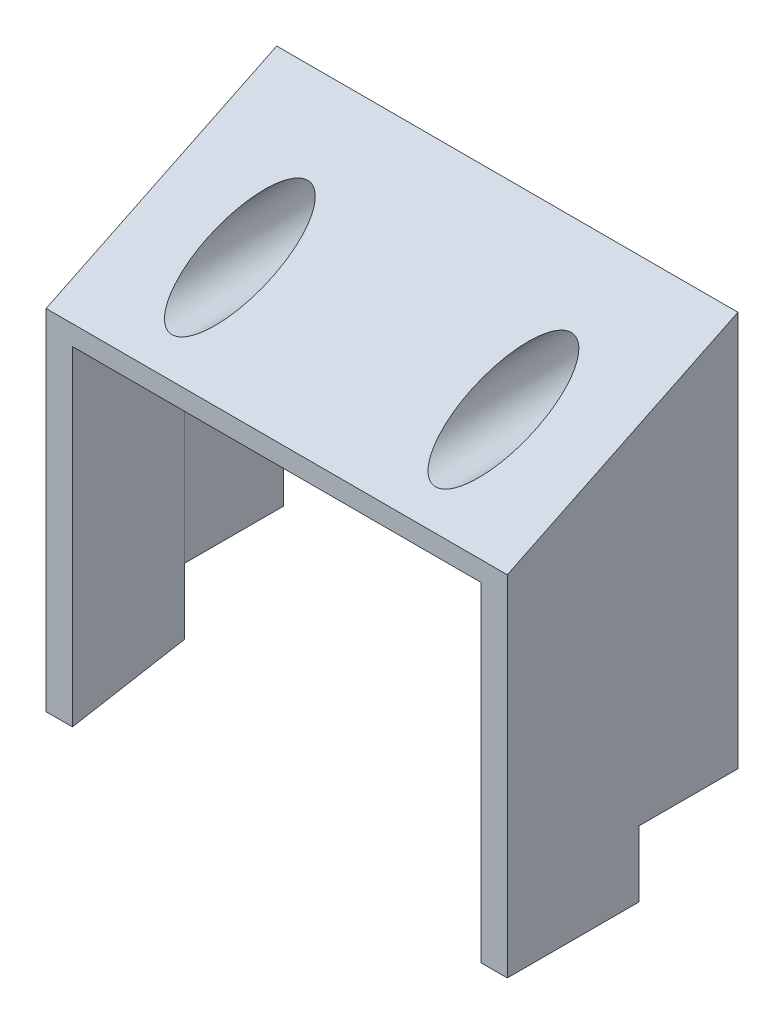
SolidWorks part; units mm, degrees
ref_plane "前视基准面" through (0, 0, 0) normal (0, 0, 1) x (1, 0, 0)
ref_plane "上视基准面" through (0, 0, 0) normal (0, 1, 0) x (1, 0, 0)
ref_plane "右视基准面" through (0, 0, 0) normal (1, 0, 0) x (0, 0, -1)
other "Configuration Table"
sketch "草图1" plane through (0, 0, 0) normal (0, 0, 1) x (1, 0, 0)
  line L0 (0, 0) -> (50000, 0) construction
  line L1 (-35, 10) -> (35, 10)
  line L2 (-35, 10) -> (-35, -10)
  line L3 (-35, -10) -> (35, -10)
  line L4 (35, 10) -> (35, -10)
  line L5 (-35, 10) -> (35, -10) construction
  line L6 (-35, -10) -> (35, 10) construction
  circle A0 centre (-20, 0) radius 3
  circle A1 centre (20, 0) radius 3
  point P0 (0, 0)
  dimension "D5" = 6
  dimension "D6" = 6
  dimension "D1" = 70
  dimension "D2" = 20
  dimension "D3" = 15
  dimension "D4" = 15
extrude "凸台-拉伸1" add sketch "草图1" along normal blind 3
sketch "草图3" plane through (0, -10, 0) normal (0, -1, 0) x (1, 0, 0)
  line L1 (-35, 0) -> (35, 0)
  line L2 (-35, 0) -> (-35, 35)
  line L3 (-35, 35) -> (35, 35)
  line L4 (35, 0) -> (35, 35)
  line L5 (35, 3) -> (35, 0) construction
  point P5 (32.6443, 25.1497)
  dimension "D1" = 35
extrude "凸台-拉伸2" add sketch "草图3" against normal blind 3
sketch "草图4" plane through (0, -10, 0) normal (0, -1, 0) x (1, 0, 0)
  line L0 (-34, 15) -> (-31, 35)
  line L1 (-35, 0) -> (-34, 0)
  line L2 (-35, 0) -> (-35, 15)
  line L4 (-34, 0) -> (-34, 15)
  line L5 (35, 0) -> (34, 0)
  line L6 (35, 0) -> (35, 15)
  line L8 (34, 0) -> (34, 15)
  line L9 (35, 35) -> (-35, 35) construction
  line L10 (-31, 35) -> (-35, 35)
  line L11 (-35, 35) -> (-35, 0) construction
  line L12 (-35, 35) -> (-35, 15)
  line L13 (35, 15) -> (35, 35)
  line L14 (35, 35) -> (31, 35)
  line L15 (31, 35) -> (34, 15)
  line L16 (-35, 15) -> (-34, 15) construction
  line L17 (34, 15) -> (35, 15) construction
  dimension "D1" = 1
  dimension "D2" = 1
  dimension "D3" = 15
  dimension "D4" = 15
  dimension "D5" = 4
  dimension "D6" = 4
extrude "凸台-拉伸3" add sketch "草图4" along normal blind 50
sketch "草图5" plane through (-35, 0, 0) normal (-1, 0, 0) x (0, 0, 1)
  line L0 (3, 10) -> (3, -7)
  line L1 (3, -7) -> (35, -7)
  line L2 (35, -7) -> (3, 10)
extrude "凸台-拉伸4" add sketch "草图5" against normal blind 70
sketch "草图6" plane through (0, 0, 3) normal (0, 0, -1) x (-1, 0, 0)
  circle A0 centre (-20, 0) radius 5
  circle A1 centre (20, 0) radius 5
  dimension "D1" = 10
  dimension "D2" = 10
extrude "切除-拉伸3" cut sketch "草图6" against normal blind 30
sketch "草图7" plane through (-35, 0, 0) normal (-1, 0, 0) x (0, 0, 1)
  line L0 (0, 10) -> (35, -7)
  line L1 (35, -7) -> (3, 10)
  line L2 (3, 10) -> (0, 10)
extrude "切除-拉伸4" cut sketch "草图7" against normal blind 70
sketch "草图8" plane through (-35, 0, 0) normal (-1, 0, 0) x (0, 0, 1)
  line L1 (0, -60) -> (15, -60)
  line L2 (0, -60) -> (0, -50)
  line L3 (0, -50) -> (15, -50)
  line L4 (15, -60) -> (15, -50)
  dimension "D1" = 10
  dimension "D2" = 15
extrude "切除-拉伸5" cut sketch "草图8" against normal through all
